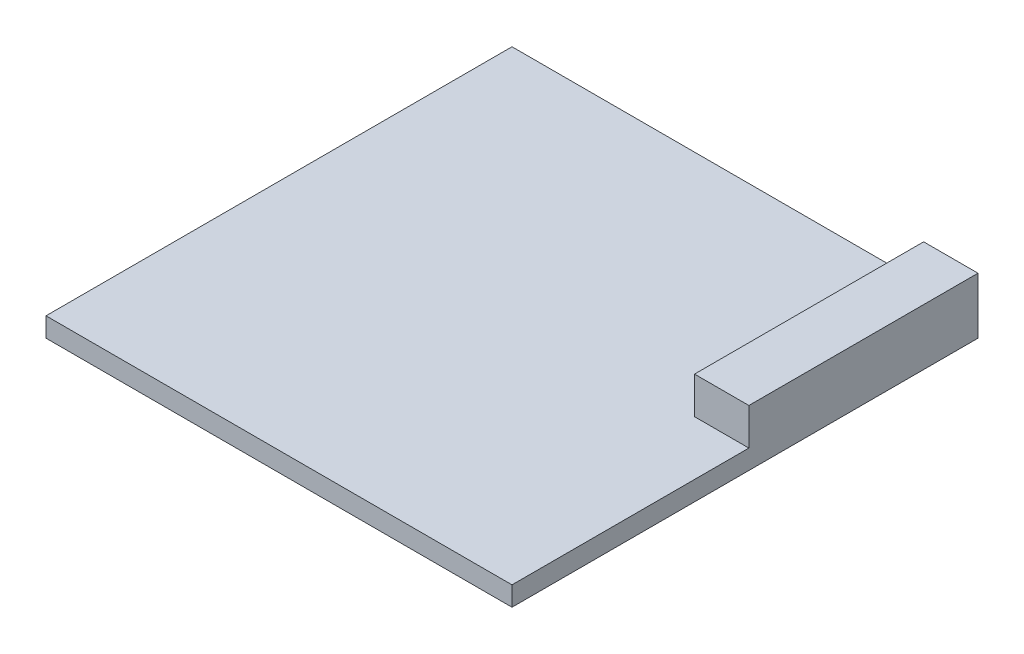
SolidWorks part; units mm, degrees
ref_plane "Front Plane" through (0, 0, 0) normal (0, 0, 1) x (1, 0, 0)
ref_plane "Top Plane" through (0, 0, 0) normal (0, 1, 0) x (1, 0, 0)
ref_plane "Right Plane" through (0, 0, 0) normal (1, 0, 0) x (0, 0, -1)
sketch "Sketch1" plane through (0, 0, 0) normal (0, 1, 0) x (1, 0, 0)
  line L1 (304.8, -304.8) -> (-304.8, -304.8)
  line L2 (304.8, -304.8) -> (304.8, 304.8)
  line L3 (304.8, 304.8) -> (-304.8, 304.8)
  line L4 (-304.8, -304.8) -> (-304.8, 304.8)
  line L5 (304.8, -304.8) -> (-304.8, 304.8) construction
  line L6 (304.8, 304.8) -> (-304.8, -304.8) construction
  point P0 (0, 0)
  dimension "D1" = 609.6
extrude "Boss-Extrude1" add sketch "Sketch1" along normal mid plane 25.4
sketch "Sketch3" plane through (0, 12.7, 0) normal (0, 1, 0) x (1, 0, 0)
  line L1 (304.8, 304.8) -> (233.68, 304.8)
  line L2 (304.8, 304.8) -> (304.8, 5.08)
  line L3 (304.8, 5.08) -> (233.68, 5.08)
  line L4 (233.68, 304.8) -> (233.68, 5.08)
  dimension "D1" = 299.72
  dimension "D2" = 71.12
extrude "Boss-Extrude2" add sketch "Sketch3" along normal blind 48.26
